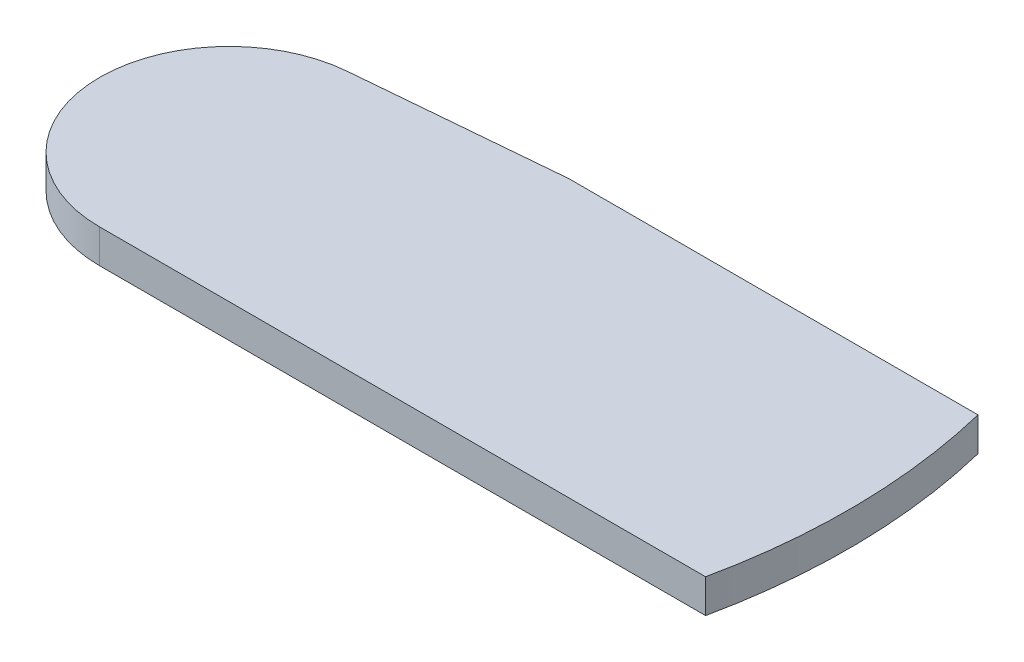
SolidWorks part; units mm, degrees
ref_plane "Płaszczyzna przednia" through (0, 0, 0) normal (0, 0, 1) x (1, 0, 0)
ref_plane "Płaszczyzna górna" through (0, 0, 0) normal (0, 1, 0) x (1, 0, 0)
ref_plane "Płaszczyzna prawa" through (0, 0, 0) normal (1, 0, 0) x (0, 0, -1)
sketch "Sketch1" plane through (0, 0, 0) normal (0, 1, 0) x (1, 0, 0)
  line L0 (-110.7065, 0) -> (22.5357, 0) construction
  line L1 (0, -110.7065) -> (0, 5424.6164) construction
  line L2 (-45.3355, 9.9619) -> (-29.5652, 11.3431)
  line L3 (-29.5652, 11.3431) -> (2.0157, 11.3431)
  line L4 (-29.5652, 11.3431) -> (-29.5652, -10)
  line L5 (-29.5652, -10) -> (2.3231, -10)
  line L7 (-44.463, -10) -> (-29.5652, -10)
  circle A0 centre (-44.463, 0) radius 10
  arc A1 (2.3231, -10) -> (2.0157, 11.3431) centre (-44.463, 0) ccw
  arc A2 (-92.2767, 7.1332) -> (-76.0312, -36.6125) centre (-44.463, 0) ccw construction
  dimension "D1" = 20
  dimension "D2" = 0.5
extrude "Boss-Extrude1" add sketch "Sketch1" along normal blind 2.6 contours A0 | A0 L7 L4 L2 | L5 A1 L3 L4
